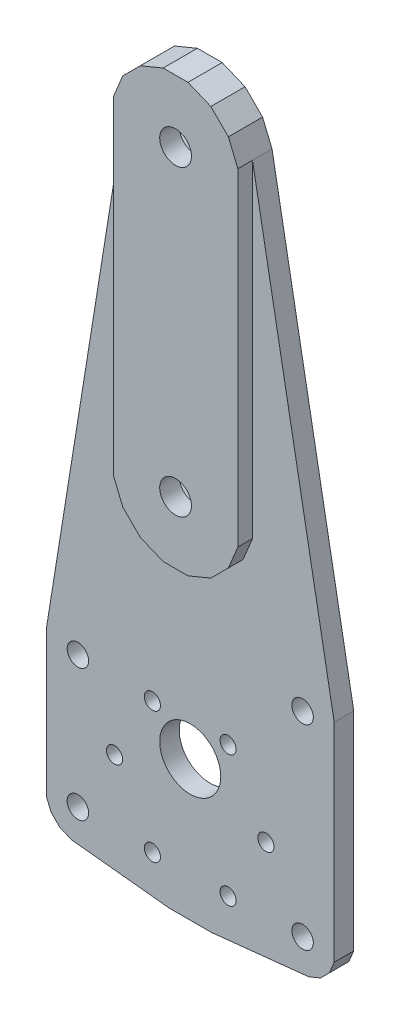
SolidWorks part; units mm, degrees
ref_plane "前视基准面" through (0, 0, 0) normal (0, 0, 1) x (1, 0, 0)
ref_plane "上视基准面" through (0, 0, 0) normal (0, 1, 0) x (1, 0, 0)
ref_plane "右视基准面" through (0, 0, 0) normal (1, 0, 0) x (0, 0, -1)
other "Configuration Table"
sketch "Profile_1" plane through (0, 0, 0) normal (0, 0, 1) x (1, 0, 0)
  line L0 (-12.7502, 2.5362) -> (-29.4732, -101.7124)
  line L1 (-29.4732, -101.7124) -> (-29.4732, -131.2876)
  line L2 (-29.4732, -131.2876) -> (-28.4877, -133.6668)
  line L3 (-28.4877, -133.6668) -> (-26.6668, -135.4877)
  line L4 (-26.6668, -135.4877) -> (-24.2876, -136.4732)
  line L5 (-24.2876, -136.4732) -> (-4.292, -138.5773)
  line L6 (-4.292, -138.5773) -> (4.292, -138.5773)
  line L7 (4.292, -138.5773) -> (24.2876, -136.4732)
  line L8 (24.2876, -136.4732) -> (26.6668, -135.4877)
  line L9 (26.6668, -135.4877) -> (28.4877, -133.6668)
  line L10 (28.4877, -133.6668) -> (29.4732, -131.2876)
  line L11 (29.4732, -131.2876) -> (29.4732, -88.7124)
  line L12 (29.4732, -88.7124) -> (12.7502, 2.5362)
  line L13 (12.7502, 2.5362) -> (10.8091, 7.2224)
  line L14 (10.8091, 7.2224) -> (7.2224, 10.8091)
  line L15 (7.2224, 10.8091) -> (2.5362, 12.7502)
  line L16 (2.5362, 12.7502) -> (-2.5362, 12.7502)
  line L17 (-2.5362, 12.7502) -> (-7.2224, 10.8091)
  line L18 (-7.2224, 10.8091) -> (-10.8091, 7.2224)
  line L19 (-10.8091, 7.2224) -> (-12.7502, 2.5362)
  circle A0 centre (0, 0) radius 3.25
  circle A1 centre (0, -62) radius 3.25
  circle A2 centre (0, -110) radius 6.25
  circle A3 centre (15.5, -117) radius 1.65
  circle A4 centre (7.75, -103.5766) radius 1.65
  circle A5 centre (-7.75, -103.5766) radius 1.65
  circle A6 centre (-15.5, -117) radius 1.65
  circle A7 centre (-7.75, -130.4234) radius 1.65
  circle A8 centre (7.75, -130.4234) radius 1.65
  circle A9 centre (-23, -130) radius 2.2
  circle A10 centre (23, -130) radius 2.2
  circle A11 centre (-23, -103) radius 2.2
  circle A12 centre (23, -90) radius 2.2
extrude "Wheel_carrier" add sketch "Profile_1" along normal blind 4 from offset 0
sketch "Profile_2" plane through (0, 0, 0) normal (0, 0, 1) x (1, 0, 0)
  line L0 (12.7502, -64.5362) -> (12.7502, 2.5362)
  line L1 (12.7502, 2.5362) -> (10.8091, 7.2224)
  line L2 (10.8091, 7.2224) -> (7.2224, 10.8091)
  line L3 (7.2224, 10.8091) -> (2.5362, 12.7502)
  line L4 (2.5362, 12.7502) -> (-2.5362, 12.7502)
  line L5 (-2.5362, 12.7502) -> (-7.2224, 10.8091)
  line L6 (-7.2224, 10.8091) -> (-10.8091, 7.2224)
  line L7 (-10.8091, 7.2224) -> (-12.7502, 2.5362)
  line L8 (-12.7502, 2.5362) -> (-12.7502, -64.5362)
  line L9 (-12.7502, -64.5362) -> (-10.8091, -69.2224)
  line L10 (-10.8091, -69.2224) -> (-7.2224, -72.8091)
  line L11 (-7.2224, -72.8091) -> (-2.5362, -74.7502)
  line L12 (-2.5362, -74.7502) -> (2.5362, -74.7502)
  line L13 (2.5362, -74.7502) -> (7.2224, -72.8091)
  line L14 (7.2224, -72.8091) -> (10.8091, -69.2224)
  line L15 (10.8091, -69.2224) -> (12.7502, -64.5362)
  circle A0 centre (0, 0) radius 3.25
  circle A1 centre (0, -62) radius 3.25
extrude "Pivot_lands" add sketch "Profile_2" along normal blind 3 from offset 4
sketch "Profile_3" plane through (0, 0, 0) normal (0, 0, 1) x (1, 0, 0)
  line L0 (5.175, 2.9878) -> (0, 5.9756)
  line L1 (0, 5.9756) -> (-5.175, 2.9878)
  line L2 (-5.175, 2.9878) -> (-5.175, -2.9878)
  line L3 (-5.175, -2.9878) -> (0, -5.9756)
  line L4 (0, -5.9756) -> (5.175, -2.9878)
  line L5 (5.175, -2.9878) -> (5.175, 2.9878)
  line L6 (5.175, -59.0122) -> (0, -56.0244)
  line L7 (0, -56.0244) -> (-5.175, -59.0122)
  line L8 (-5.175, -59.0122) -> (-5.175, -64.9878)
  line L9 (-5.175, -64.9878) -> (0, -67.9756)
  line L10 (0, -67.9756) -> (5.175, -64.9878)
  line L11 (5.175, -64.9878) -> (5.175, -59.0122)
extrude "Nut_seats_C_D" cut sketch "Profile_3" along normal blind 3.01 from offset 0.01
